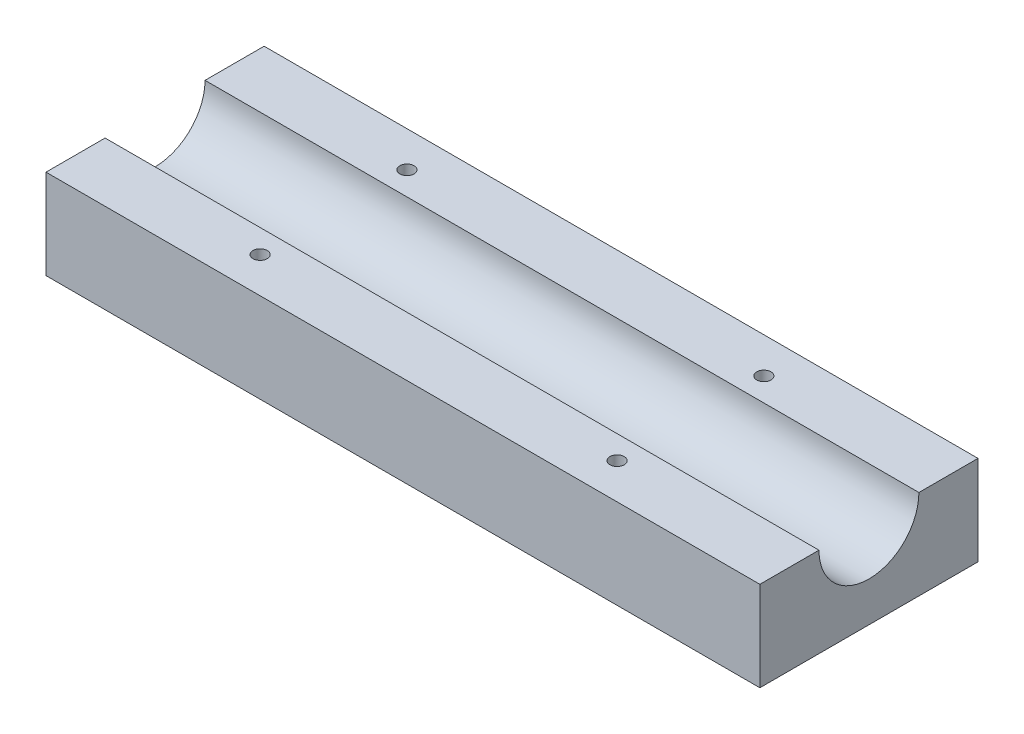
SolidWorks part; units mm, degrees
ref_plane "Front Plane" through (0, 0, 0) normal (0, 0, 1) x (1, 0, 0)
ref_plane "Top Plane" through (0, 0, 0) normal (0, 1, 0) x (1, 0, 0)
ref_plane "Right Plane" through (0, 0, 0) normal (1, 0, 0) x (0, 0, -1)
sketch "Sketch1" plane through (0, 0, 0) normal (0, 1, 0) x (1, 0, 0)
  line L1 (-105.8865, -40.0153) -> (122.7135, -40.0153)
  line L2 (-105.8865, -40.0153) -> (-105.8865, 29.8347)
  line L3 (-105.8865, 29.8347) -> (122.7135, 29.8347)
  line L4 (122.7135, -40.0153) -> (122.7135, 29.8347)
  dimension "D1" = 228.6
  dimension "2.75" = 69.85
extrude "Boss-Extrude1" add sketch "Sketch1" along normal blind 28.702
sketch "Sketch2" plane through (122.7135, 0, 0) normal (1, 0, 0) x (0, 0, -1)
  line L0 (-40.0153, 28.702) -> (29.8347, 28.702) construction
  circle A0 centre (-5.0903, 28.702) radius 16.002
  dimension "D1" = 32.004
extrude "Cut-Extrude1" cut sketch "Sketch2" against normal through all
sketch "Sketch3" plane through (0, 28.702, 0) normal (0, 1, 0) x (1, 0, 0)
  line L0 (-105.8865, 29.8347) -> (8.4135, 29.8347)
  line L1 (122.7135, 29.8347) -> (-105.8865, 29.8347) construction
  line L2 (8.4135, 29.8347) -> (8.4135, -40.0153)
  line L3 (-105.8865, -40.0153) -> (122.7135, -40.0153) construction
  line L4 (-105.8865, 18.4153) -> (8.4135, 18.4153)
  line L5 (-105.8865, 29.8347) -> (-105.8865, 10.9117) construction
  line L6 (-48.7365, 29.8347) -> (-48.7365, -40.0153)
  line L7 (-105.8865, -5.0903) -> (122.7135, -5.0903)
  line L8 (-105.8865, 10.9117) -> (-105.8865, -21.0923) construction
  line L9 (122.7135, -21.0923) -> (122.7135, 10.9117) construction
  circle A0 centre (-48.7365, 18.4153) radius 2.286
  circle A1 centre (-48.7365, -28.5958) radius 2.286
  circle A2 centre (65.5635, 18.4153) radius 2.286
  circle A3 centre (65.5635, -28.5958) radius 2.286
  dimension "D1" = 4.572
extrude "Cut-Extrude2" cut sketch "Sketch3" against normal through all contours A0 | A1 | A3 | A2
sketch "Sketch4" plane through (0, 0, 0) normal (0, -1, 0) x (1, 0, 0)
  line L0 (-105.8865, 5.0903) -> (122.7135, 5.0903)
  line L5 (-105.8865, -29.8347) -> (-105.8865, 40.0153) construction
  line L6 (122.7135, 40.0153) -> (122.7135, -29.8347) construction
  line L7 (8.4135, 40.0153) -> (8.4135, -29.8347)
  line L8 (-105.8865, 40.0153) -> (122.7135, 40.0153) construction
  line L9 (122.7135, -29.8347) -> (-105.8865, -29.8347) construction
  line L20 (-49.7885, 31.0901) -> (-47.6843, 31.0901)
  line L21 (-46.1964, -19.4217) -> (-47.6843, -20.9095)
  line L22 (-51.2764, 29.6022) -> (-49.7885, 31.0901)
  line L23 (-46.1964, -17.3174) -> (-47.6843, -15.8295)
  line L24 (-51.2764, 27.498) -> (-49.7885, 26.0101)
  line L25 (-51.2764, 27.498) -> (-51.2764, 29.6022)
  line L26 (-49.7885, 26.0101) -> (-47.6843, 26.0101)
  line L28 (-46.1964, -17.3174) -> (-46.1964, -19.4217)
  line L29 (-49.7885, -15.8295) -> (-47.6843, -15.8295)
  line L30 (-46.1964, 27.498) -> (-46.1964, 29.6022)
  line L31 (-46.1964, 27.498) -> (-47.6843, 26.0101)
  line L32 (-51.2764, -17.3174) -> (-51.2764, -19.4217)
  line L33 (-46.1964, 29.6022) -> (-47.6843, 31.0901)
  line L34 (-51.2764, -17.3174) -> (-49.7885, -15.8295)
  line L35 (-51.2764, -19.4217) -> (-49.7885, -20.9095)
  line L36 (-49.7885, -20.9095) -> (-47.6843, -20.9095)
  line L37 (66.6154, -20.9095) -> (64.5112, -20.9095)
  line L38 (68.1033, -19.4217) -> (66.6154, -20.9095)
  line L39 (68.1033, -17.3174) -> (66.6154, -15.8295)
  line L40 (63.0233, 29.6022) -> (64.5112, 31.0901)
  line L41 (68.1033, -17.3174) -> (68.1033, -19.4217)
  line L42 (63.0233, 27.498) -> (64.5112, 26.0101)
  line L43 (63.0233, 27.498) -> (63.0233, 29.6022)
  line L44 (66.6154, -15.8295) -> (64.5112, -15.8295)
  line L45 (63.0233, -17.3174) -> (63.0233, -19.4217)
  line L46 (66.6154, 26.0101) -> (64.5112, 26.0101)
  line L47 (68.1033, 27.498) -> (68.1033, 29.6022)
  line L48 (68.1033, 27.498) -> (66.6154, 26.0101)
  line L49 (63.0233, -17.3174) -> (64.5112, -15.8295)
  line L50 (68.1033, 29.6022) -> (66.6154, 31.0901)
  line L51 (63.0233, -19.4217) -> (64.5112, -20.9095)
  line L52 (66.6154, 31.0901) -> (64.5112, 31.0901)
  dimension "D3" = 5.08
  dimension "D2" = 5.08
  dimension "D1" = 5.08
  dimension "D4" = 5.08
extrude "Cut-Extrude3" cut sketch "Sketch4" against normal blind 2.54 contours L31 L26 L24 L25 L22 L20 L33 L30 | L21 L36 L35 L32 L34 L29 L23 L28 | L37 L51 L45 L49 L44 L39 L41 L38 | L46 L42 L43 L40 L52 L50 L47 L48
